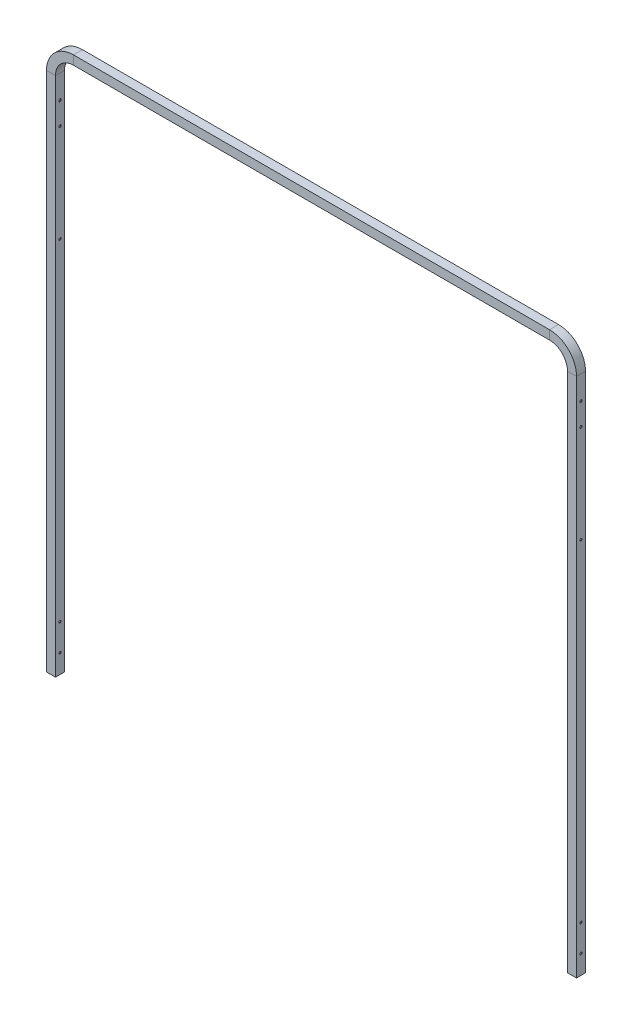
SolidWorks part; units mm, degrees
ref_plane "Front Plane" through (0, 0, 0) normal (0, 0, 1) x (1, 0, 0)
ref_plane "Top Plane" through (0, 0, 0) normal (0, 1, 0) x (1, 0, 0)
ref_plane "Right Plane" through (0, 0, 0) normal (1, 0, 0) x (0, 0, -1)
sketch "Sketch1" plane through (0, 0, 0) normal (0, 0, 1) x (1, 0, 0)
  line L0 (0, 0) -> (0, 1160)
  line L1 (50, 1210) -> (1110, 1210)
  line L2 (1160, 1160) -> (1160, 0)
  arc A0 (1160, 1160) -> (1110, 1210) centre (1110, 1160) ccw
  arc A1 (0, 1160) -> (50, 1210) centre (50, 1160) cw
  dimension "D3" = 50
  dimension "D1" = 1160
  dimension "D2" = 1210
other "Al tube square AL TUBE 0.75 SQR X 0.065 WALL(1)"
ref_plane "Plane1" through (0, 0, 0) normal (0, 1, 0) x (-1, 0, 0)
sketch "Sketch15" plane through (0, 0, 0) normal (0, 1, 0) x (-1, 0, 0)
  line L0 (-8.8, -8.8) -> (-8.8, 8.8)
  line L1 (8.8, 8.8) -> (-8.8, 8.8)
  line L2 (8.8, 8.8) -> (8.8, -8.8)
  line L3 (-8.8, -8.8) -> (8.8, -8.8)
  line L4 (-10, -10) -> (10, -10)
  line L5 (-10, -10) -> (-10, 10)
  line L6 (10, 10) -> (-10, 10)
  line L7 (10, 10) -> (10, -10)
  line L8 (0, -8.8) -> (0, -10) construction
  line L9 (0, -8.8) -> (0, 8.8) construction
  line L10 (0, 8.8) -> (0, 10) construction
  line L11 (10, 0) -> (8.8, 0) construction
  line L12 (8.8, 0) -> (-8.8, 0) construction
  line L13 (-8.8, 0) -> (-10, 0) construction
  point P14 (0, 0)
  point P17 (0, 0)
  dimension "Thickness" = 1.2
  dimension "V_leg" = 20
  dimension "H_leg" = 20
sketch "Sketch16" plane through (1170, 0, -1160) normal (1, 0, 0) x (0, 0, -1)
  line L0 (-1160, 0) -> (-1160, 1160) construction
  line L3 (-1170, 1160) -> (-1150, 1160) construction
  line L4 (-1150, 0) -> (-1170, 0) construction
  circle A0 centre (-1160, 1107.5) radius 2.75
  circle A1 centre (-1160, 1057.5) radius 2.75
  dimension "D1" = 5.5
  dimension "D2" = 1057.5
  dimension "D3" = 50
extrude "Cut-Extrude1" cut sketch "Sketch16" against normal through all
sketch "Sketch17" plane through (1170, 0, 0) normal (1, 0, 0) x (0, 0, -1)
  line L0 (0, 1107.5) -> (0, 1057.5) construction
  line L1 (0, 1082.5) -> (27.5348, 1082.5) construction
ref_plane "Plane2" through (0, 1082.5, 0) normal (0, 1, 0) x (1, 0, 0)
sketch "Sketch18" plane through (1170, 0, 0) normal (1, 0, 0) x (0, 0, -1)
  line L0 (0, 102) -> (0, 42) construction
  circle A0 centre (0, 102) radius 2.5
  circle A1 centre (0, 42) radius 2.5
  dimension "D1" = 5
extrude "Cut-Extrude2" cut sketch "Sketch18" against normal through all
sketch "Sketch19" plane through (-10, 0, 0) normal (-1, 0, 0) x (0, 0, 1)
  circle A0 centre (0, 840.1245) radius 2.5
  circle A2 centre (0, 840.1245) radius 3.125 construction
  circle A3 centre (0, 840.1245) radius 3.125 construction
  dimension "D1" = 5
extrude "Cut-Extrude3" cut sketch "Sketch19" against normal through all
